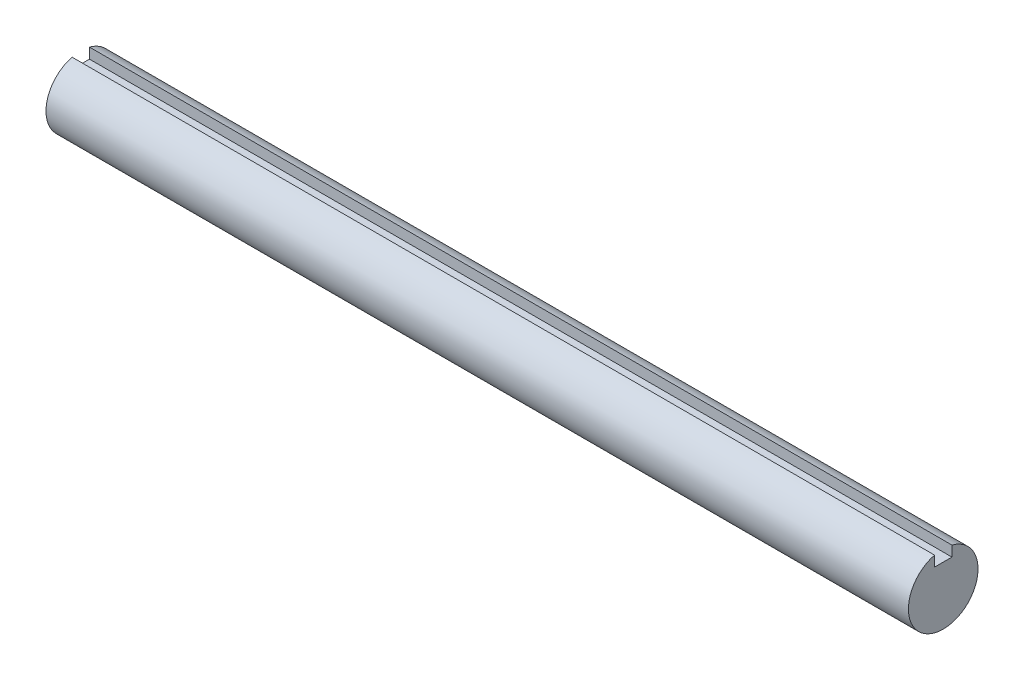
SolidWorks part; units mm, degrees
ref_plane "Front" through (0, 0, 0) normal (0, 0, 1) x (1, 0, 0)
ref_plane "Top" through (0, 0, 0) normal (0, 1, 0) x (1, 0, 0)
ref_plane "Right" through (0, 0, 0) normal (1, 0, 0) x (0, 0, -1)
sketch "Sketch1" plane through (0, 0, 0) normal (1, 0, 0) x (0, 0, -1)
  line L2 (-1, 3.873) -> (-1, 2.673)
  line L3 (-1, 2.673) -> (1, 2.673)
  line L4 (1, 3.873) -> (1, 2.673)
  arc A0 (-1, 3.873) -> (1, 3.873) centre (0, 0) ccw
  point P7 (0, 2.673)
  dimension "D1" = 8
  dimension "D2" = 2
  dimension "D3" = 1.2
extrude "Boss-Extrude1" add sketch "Sketch1" along normal up to surface (99.1235 mm away)
